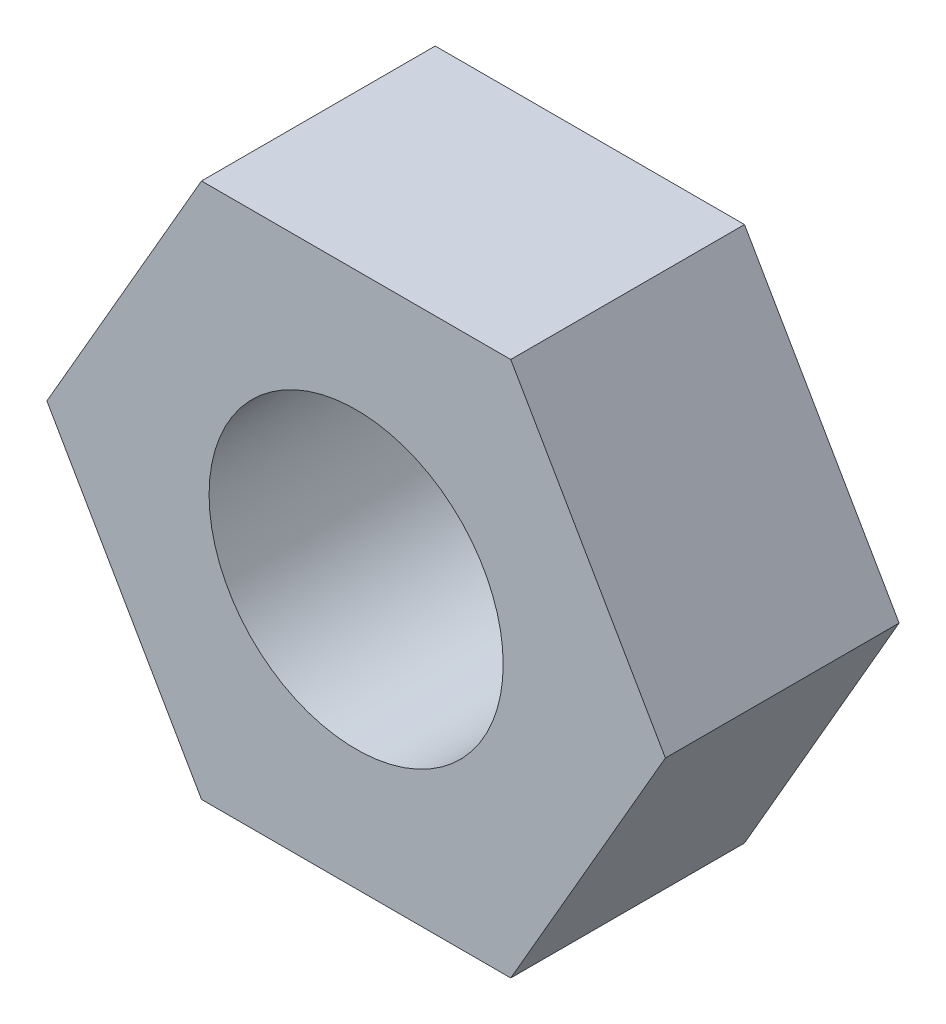
SolidWorks part; units mm, degrees
ref_plane "前视基准面" through (0, 0, 0) normal (0, 0, 1) x (1, 0, 0)
ref_plane "上视基准面" through (0, 0, 0) normal (0, 1, 0) x (1, 0, 0)
ref_plane "右视基准面" through (0, 0, 0) normal (1, 0, 0) x (0, 0, -1)
other "Configuration Table"
sketch "ISO4032_M3_AF5p5_h2p4_Sketch" plane through (0, 0, 0) normal (0, 0, 1) x (1, 0, 0)
  line L0 (3.1754, 0) -> (1.5877, 2.75)
  line L1 (1.5877, 2.75) -> (-1.5877, 2.75)
  line L2 (-1.5877, 2.75) -> (-3.1754, 0)
  line L3 (-3.1754, 0) -> (-1.5877, -2.75)
  line L4 (-1.5877, -2.75) -> (1.5877, -2.75)
  line L5 (1.5877, -2.75) -> (3.1754, 0)
  circle A0 centre (0, 0) radius 1.51
extrude "ISO4032_M3_AF5p5_h2p4" add sketch "ISO4032_M3_AF5p5_h2p4_Sketch" along normal blind 2.4 separate body
